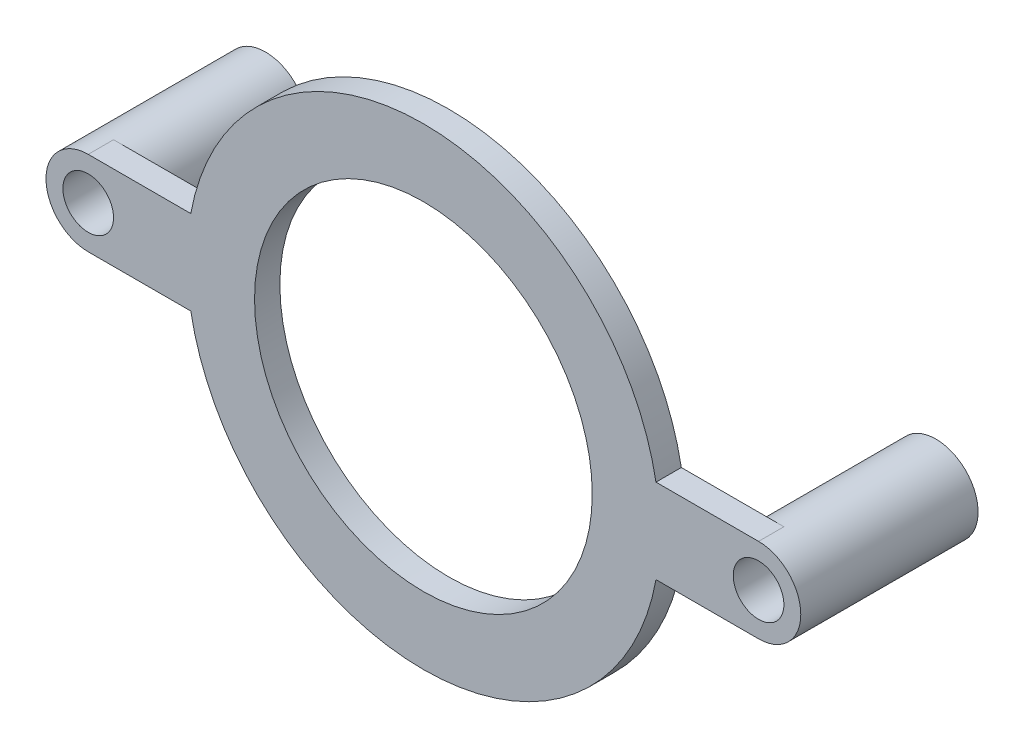
SolidWorks part; units mm, degrees
ref_plane "Plano frontal" through (0, 0, 0) normal (0, 0, 1) x (1, 0, 0)
ref_plane "Plano superior" through (0, 0, 0) normal (0, 1, 0) x (1, 0, 0)
ref_plane "Plano direito" through (0, 0, 0) normal (1, 0, 0) x (0, 0, -1)
ref_plane "Plano1" through (0, 0, 0) normal (0, 0, -1) x (-1, 0, 0)
sketch "Esboço1" plane through (0, 0, 0) normal (0, 0, -1) x (-1, 0, 0)
  line L0 (13.775, -2.5) -> (19.85, -2.5)
  line L1 (19.85, 2.5) -> (13.775, 2.5)
  line L2 (-13.775, 2.5) -> (-19.85, 2.5)
  line L3 (-19.85, -2.5) -> (-13.775, -2.5)
  arc A0 (19.85, -2.5) -> (19.85, 2.5) centre (19.85, 0) ccw
  arc A1 (13.775, 2.5) -> (-13.775, 2.5) centre (0, 0) ccw
  arc A2 (-19.85, 2.5) -> (-19.85, -2.5) centre (-19.85, 0) ccw
  arc A3 (-13.775, -2.5) -> (13.775, -2.5) centre (0, 0) ccw
extrude "Ressalto-extrusão1" add sketch "Esboço1" against normal blind 1.5
sketch "Esboço2" plane through (0, 0, 0) normal (0, 0, -1) x (-1, 0, 0)
  circle A0 centre (-19.85, 0) radius 2.5
extrude "Ressalto-extrusão2" add sketch "Esboço2" along normal blind 22
sketch "Esboço3" plane through (0, 0, 0) normal (0, 0, -1) x (-1, 0, 0)
  circle A0 centre (19.85, 0) radius 2.5
extrude "Ressalto-extrusão3" add sketch "Esboço3" along normal blind 22
hole_wizard "Furo de diâmetro Ø3.0 (3)1" positions "Esboço5" profile "Esboço4" hole size "Ø3.0" standard "Ansi Metric"
sketch "Esboço5" plane through (0, 0, -22) normal (0, 0, -1) x (-1, 0, 0)
  point P0 (-19.85, 0)
  point P1 (19.85, 0)
sketch "Esboço4" plane through (19.85, 0, -22) normal (1, 0, 0) x (0, 1, 0)
  line L0 (0, 0) -> (0, 23.5)
  line L1 (0, 23.5) -> (1.5, 23.5)
  line L2 (1.5, 23.5) -> (1.5, 0)
  line L5 (1.5, 0) -> (0, 0)
  line L11 (0, -6.35) -> (0, 107.95) construction
  dimension "Thru Hole Dia." = 3
  dimension "Thru Hole Depth" = 23.5
hole_wizard "Furo de diâmetro Ø20.0 (20)1" positions "Esboço7" profile "Esboço6" hole size "Ø20.0" standard "Ansi Metric"
sketch "Esboço7" plane through (0, 0, 1.5) normal (0, 0, 1) x (1, 0, 0)
  point P0 (0, 0)
sketch "Esboço6" plane through (0, 0, 1.5) normal (1, 0, 0) x (0, -1, 0)
  line L0 (0, 0) -> (0, 23.5)
  line L1 (0, 23.5) -> (10, 23.5)
  line L2 (10, 23.5) -> (10, 0)
  line L5 (10, 0) -> (0, 0)
  line L11 (0, -6.35) -> (0, 107.95) construction
  dimension "Thru Hole Dia." = 20
  dimension "Thru Hole Depth" = 23.5
sketch "Esboço8" plane through (0, 0, -22) normal (0, 0, -1) x (-1, 0, 0)
  circle A0 centre (19.85, 0) radius 2.5
  circle A1 centre (19.85, 0) radius 1.5
  circle A2 centre (-19.85, 0) radius 1.5
  circle A3 centre (-19.85, 0) radius 2.5
extrude "Corte-extrusão1" cut sketch "Esboço8" against normal blind 13 contours A0 | A3
